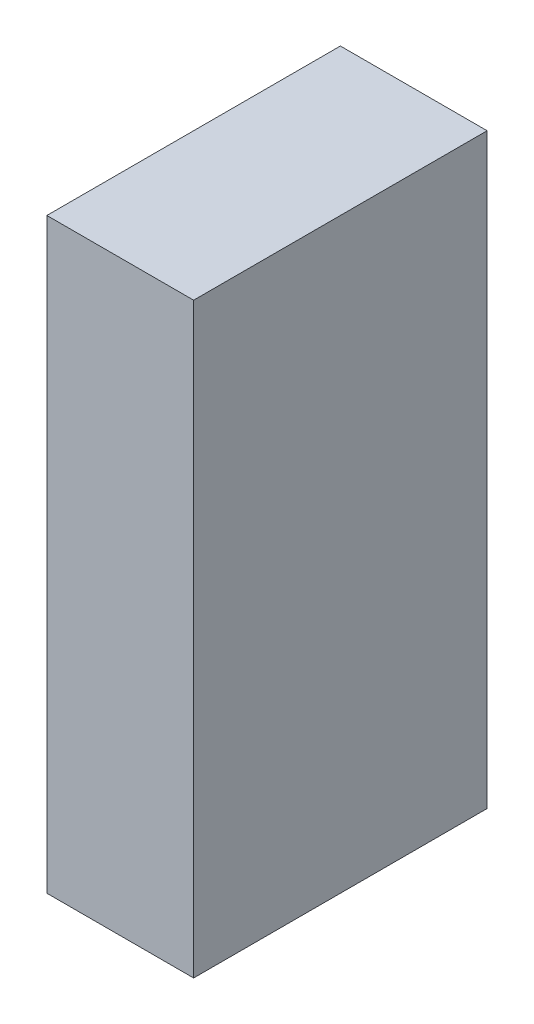
SolidWorks part; units mm, degrees
ref_plane "Front Plane" through (0, 0, 0) normal (0, 0, 1) x (1, 0, 0)
ref_plane "Top Plane" through (0, 0, 0) normal (0, 1, 0) x (1, 0, 0)
ref_plane "Right Plane" through (0, 0, 0) normal (1, 0, 0) x (0, 0, -1)
sketch "RectangleSketch" plane through (0, 0, 0) normal (1, 0, 0) x (0, 0, -1)
  line L1 (0, 0) -> (-20, 0)
  line L2 (0, 0) -> (0, 40)
  line L3 (0, 40) -> (-20, 40)
  line L4 (-20, 0) -> (-20, 40)
  dimension "width_mm" = 40
  dimension "height_mm" = 20
extrude "BlindBoss" add sketch "RectangleSketch" along normal blind 10 separate body
